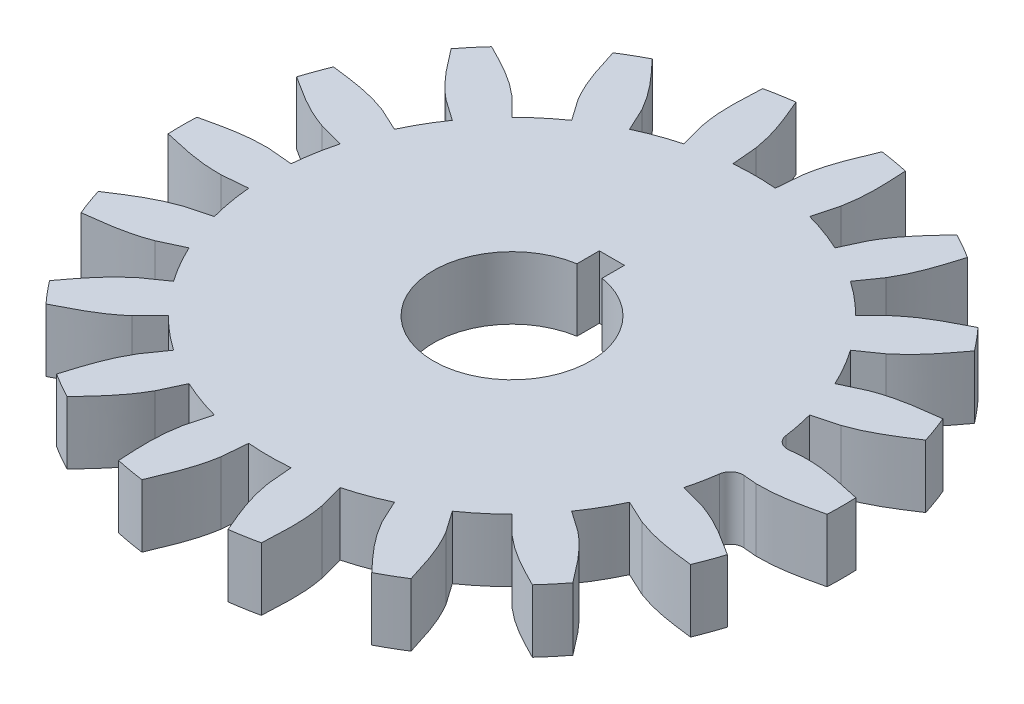
SolidWorks part; units mm, degrees
ref_plane "Alzado" through (0, 0, 0) normal (0, 0, 1) x (1, 0, 0)
ref_plane "Planta" through (0, 0, 0) normal (0, 1, 0) x (1, 0, 0)
ref_plane "Vista lateral" through (0, 0, 0) normal (1, 0, 0) x (0, 0, -1)
sketch "Croquis1" plane through (0, 0, 0) normal (0, 1, 0) x (1, 0, 0)
  line L0 (0, 0) -> (69.6585, 0) construction
  line L1 (0, 0) -> (69.9099, 12.327) construction
  line L2 (0, 0) -> (63.7737, 5.5795) construction
  line L3 (0, 0) -> (63.7687, 2.7842) construction
  line L4 (42.604, 3.7274) -> (38.5461, 3.3723)
  line L5 (41.7042, 3.7274) -> (43.5038, 3.7274) construction
  line L6 (38.1055, 6.719) -> (0, 0)
  line L7 (42.604, -3.7274) -> (38.5461, -3.3723)
  line L8 (38.1055, -6.719) -> (0, 0)
  circle A0 centre (0, 0) radius 52.5 construction
  circle A1 centre (0, 0) radius 45.285 construction
  circle A2 centre (0, 0) radius 36.25 construction
  arc A3 (38.5461, 3.3723) -> (38.1055, 6.719) centre (0, 0) ccw
  arc A4 (52.4628, 2.2906) -> (52.4628, -2.2906) centre (0, 0) cw
  arc A5 (38.5461, -3.3723) -> (38.1055, -6.719) centre (0, 0) cw
  spline S0 degree 3 poles (52.4628, 2.2906) (46.9902, 3.589) (45.1935, 3.7274) (42.604, 3.7274) knots 0 0 0 0 1 1 1 1
  spline S1 degree 3 poles (52.4628, -2.2906) (46.9902, -3.589) (45.1935, -3.7274) (42.604, -3.7274) knots 0 0 0 0 1 1 1 1
  dimension "D1" = 105
  dimension "D2" = 90.57
  dimension "D3" = 16.25
  dimension "D4" = 10
  dimension "D5" = 5
  dimension "D6" = 2.5
extrude "Saliente-Extruir1" add sketch "Croquis1" along normal blind 10
fillet "Redondeo1" radius 2 2 edges at (38.5461, 5, 3.3723) (38.5461, 5, -3.3723)
pattern_circular "MatrizC4" count 18 over 360 about axis through (0, 10, 0) along (0, -1, 0) of "Saliente-Extruir1"
sketch "Croquis3" plane through (0, 10, 0) normal (0, 1, 0) x (1, 0, 0)
  line L0 (0, 0) -> (0, 22.7102) construction
  line L1 (2, 22.7102) -> (2, 0) construction
  line L2 (0, 0) -> (69.6585, 0) construction
  line L3 (-2, 22.7102) -> (-2, 0) construction
  line L4 (-2, 15.9031) -> (-2, 12.339)
  line L5 (-2, 15.9031) -> (2, 15.9031)
  line L6 (2, 15.9031) -> (2, 12.339)
  arc A0 (-2, 12.339) -> (2, 12.339) centre (0, 0) ccw
  dimension "D1" = 25
  dimension "D2" = 2
  dimension "D3" = 2
extrude "Cortar-Extruir1" cut sketch "Croquis3" against normal blind 10
